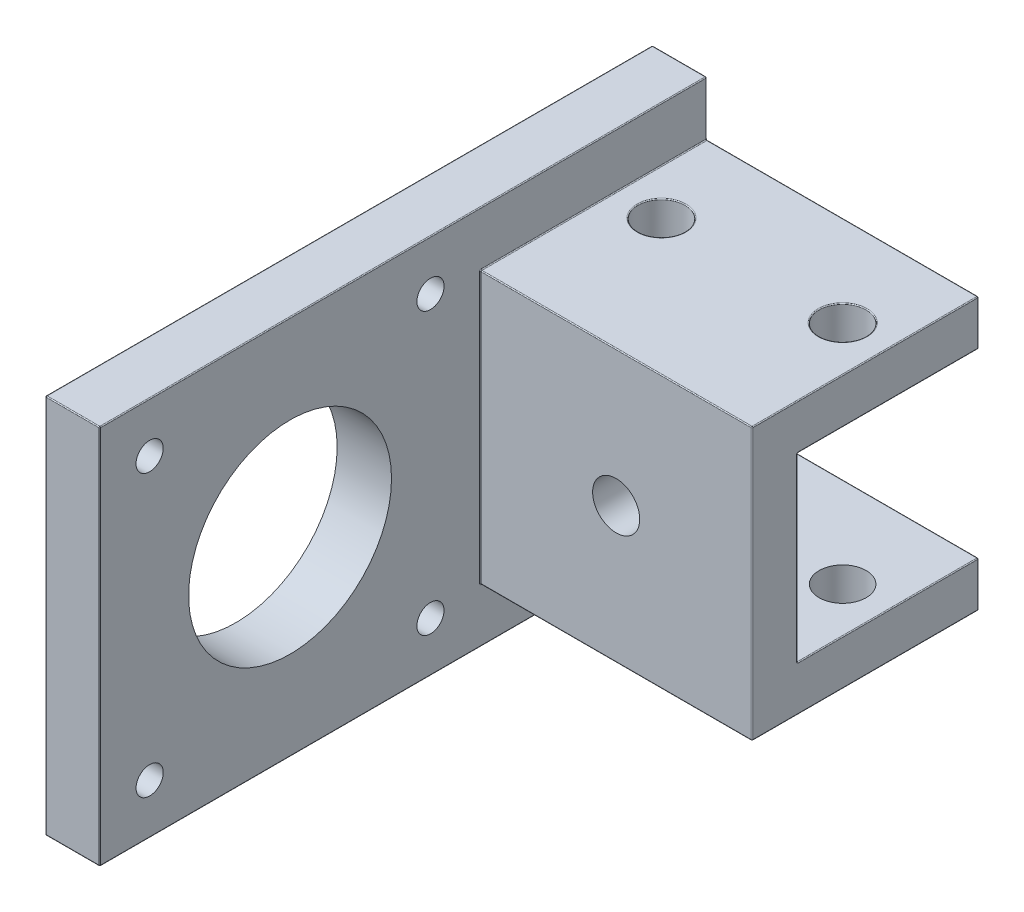
SolidWorks part; units mm, degrees
ref_plane "Front Plane" through (0, 0, 0) normal (0, 0, 1) x (1, 0, 0)
ref_plane "Top Plane" through (0, 0, 0) normal (0, 1, 0) x (1, 0, 0)
ref_plane "Right Plane" through (0, 0, 0) normal (1, 0, 0) x (0, 0, -1)
ref_plane "Plane1" through (45.0281, 0, 0) normal (1, 0, 0) x (0, 0, -1)
sketch "Sketch1" plane through (45.0281, 0, 0) normal (1, 0, 0) x (0, 0, -1)
  line L0 (-47, 0) -> (20, 0)
  line L1 (20, 0) -> (20, 42)
  line L2 (20, 42) -> (-47, 42)
  line L3 (-47, 42) -> (-47, 0)
  dimension "D1" = 67
  dimension "D2" = 42
  dimension "D3" = 20
  dimension "D4" = 42
extrude "Boss-Extrude1" add sketch "Sketch1" against normal blind 6
sketch "Sketch2" plane through (45.0281, 0, 0) normal (1, 0, 0) x (0, 0, -1)
  line L0 (20, 36) -> (20, 6)
  line L1 (20, 6) -> (-5, 6)
  line L2 (-5, 6) -> (-5, 36)
  line L3 (-5, 36) -> (20, 36)
  line L4 (-47, 0) -> (20, 0) construction
  dimension "D1" = 25
  dimension "D2" = 30
  dimension "D3" = 42
  dimension "D4" = 6
extrude "Boss-Extrude2" add sketch "Sketch2" along normal blind 30
sketch "Sketch3" plane through (39.0281, 0, 0) normal (-1, 0, 0) x (0, 0, 1)
  line L0 (-20, 31) -> (-20, 11)
  line L1 (-20, 11) -> (0, 11)
  line L2 (0, 11) -> (0, 31)
  line L3 (0, 31) -> (-20, 31)
  line L4 (47, 42) -> (47, 0) construction
  line L5 (-20, 42) -> (47, 42) construction
  dimension "D1" = 47
  dimension "D2" = 67
  dimension "D3" = 11
extrude "Cut-Extrude1" cut sketch "Sketch3" against normal through all
sketch "Sketch14" plane through (45.0281, 0, 0) normal (1, 0, 0) x (0, 0, -1)
  line L0 (-5, 36) -> (-5, 6) construction
  line L1 (-47, 21) -> (-5, 21) construction
  line L2 (-47, 42) -> (-47, 0) construction
  circle A2 centre (-26, 21) radius 11.2
  dimension "D1" = 22.4
  dimension "D2" = 21
extrude "Cut-Extrude12" cut sketch "Sketch14" against normal blind 10
sketch "Sketch15" plane through (0, 6, 0) normal (0, -1, 0) x (-1, 0, 0)
  line L0 (-75.0281, 20) -> (-45.0281, 20) construction
  line L1 (-45.0281, -5) -> (-45.0281, 20) construction
  circle A0 centre (-50.0281, 10) radius 2.6
  circle A1 centre (-70.0281, 10) radius 2.6
  dimension "D1" = 5.2
  dimension "D2" = 10
  dimension "D5" = 20
  dimension "D3" = 5
  dimension "D4" = 2
extrude "Cut-Extrude13" cut sketch "Sketch15" against normal through all
sketch "Sketch18" plane through (45.0281, 0, 0) normal (1, 0, 0) x (0, 0, -1)
  circle A0 centre (-10.5, 36.5) radius 1.5 construction
  circle A1 centre (-10.5, 5.5) radius 1.5 construction
  circle A2 centre (-41.5, 5.5) radius 1.5 construction
  circle A3 centre (-41.5, 36.5) radius 1.5 construction
  circle A4 centre (-10.5, 36.5) radius 1.5
  circle A5 centre (-10.5, 5.5) radius 1.5
  circle A6 centre (-41.5, 5.5) radius 1.5
  circle A7 centre (-41.5, 36.5) radius 1.5
extrude "Cut-Extrude14" cut sketch "Sketch18" against normal through all
sketch "Sketch19" plane through (0, 0, 5) normal (0, 0, 1) x (1, 0, 0)
  line L0 (60.0281, 36) -> (60.0281, 6) construction
  line L1 (75.0281, 36) -> (45.0281, 36) construction
  line L2 (75.0281, 6) -> (45.0281, 6) construction
  line L3 (75.0281, 21) -> (45.0281, 21) construction
  line L4 (75.0281, 36) -> (75.0281, 6) construction
  line L5 (45.0281, 36) -> (45.0281, 6) construction
  circle A0 centre (60.0281, 21) radius 2.6
  dimension "D1" = 5.2
extrude "Cut-Extrude15" cut sketch "Sketch19" against normal through all
fillet "Fillet1" radius 0.1 42 edges at (39.0281, 5.5, -20) (45.0281, 39, -20) (45.0281, 36, -7.5) (39.0281, 42, 13.5) (60.0281, 36, -20) (45.0281, 21, 5) (60.0281, 36, 5) (45.0281, 6, -7.5) (60.0281, 6, 5) (60.0281, 6, -20) (75.0281, 36, -7.5) (75.0281, 21, 5) (75.0281, 6, -7.5) (75.0281, 8.5, -20) (75.0281, 33.5, -20) (39.0281, 36.5, -20) (75.0281, 31, -10) (57.0281, 31, -20) (75.0281, 21, 0) (57.0281, 31, 0) (75.0281, 11, -10) (57.0281, 11, 0) (57.0281, 11, -20) (39.0281, 31, -10) (39.0281, 11, -10) (39.0281, 21, 0) (39.0281, 21, 47) (45.0281, 42, 13.5) (45.0281, 3, -20) (50.0281, 31, -7.4) (50.0281, 36, -12.6) (50.0281, 6, -12.6) (45.0281, 0, 13.5) (70.0281, 31, -7.4) (70.0281, 36, -12.6) (70.0281, 6, -12.6) (45.0281, 21, 47) (42.0281, 42, 47) (42.0281, 42, -20) (42.0281, 0, -20) (42.0281, 0, 47) (39.0281, 0, 13.5)
